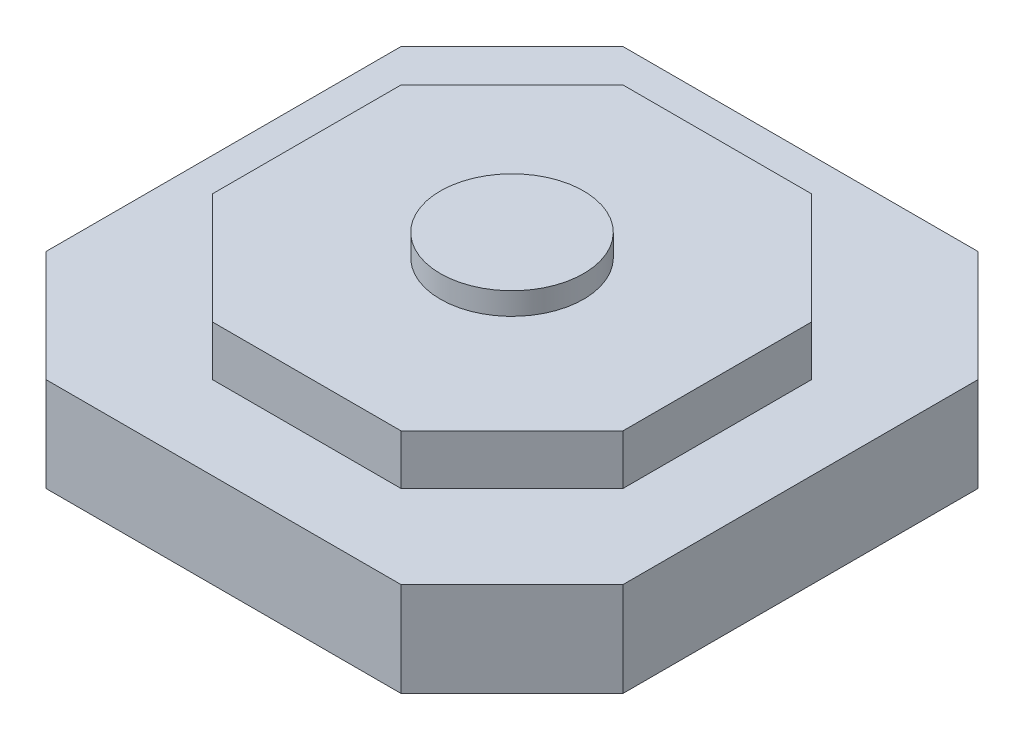
SolidWorks part; units mm, degrees
ref_plane "前视基准面" through (0, 0, 0) normal (0, 0, 1) x (1, 0, 0)
ref_plane "上视基准面" through (0, 0, 0) normal (0, 1, 0) x (1, 0, 0)
ref_plane "右视基准面" through (0, 0, 0) normal (1, 0, 0) x (0, 0, -1)
sketch "草图1" plane through (0, 0, 0) normal (0, 1, 0) x (1, 0, 0)
  line L1 (-2.6, 2.6) -> (2.6, 2.6)
  line L2 (-2.6, 2.6) -> (-2.6, -2.6)
  line L3 (-2.6, -2.6) -> (2.6, -2.6)
  line L4 (2.6, 2.6) -> (2.6, -2.6)
  line L5 (-2.6, 2.6) -> (2.6, -2.6) construction
  line L6 (-2.6, -2.6) -> (2.6, 2.6) construction
  point P0 (0, 0)
  dimension "D1" = 5.2
  dimension "D2" = 5.2
extrude "凸台-拉伸1" add sketch "草图1" along normal blind 0.85
chamfer "倒角1" distance 1 angle 45 4 edges at (-2.6, 0.425, -2.6) (2.6, 0.425, -2.6) (2.6, 0.425, 2.6) (-2.6, 0.425, 2.6)
sketch "草图2" plane through (0, 0.85, 0) normal (0, 1, 0) x (1, 0, 0)
  line L1 (-1.85, 1.85) -> (1.85, 1.85)
  line L2 (-1.85, 1.85) -> (-1.85, -1.85)
  line L3 (-1.85, -1.85) -> (1.85, -1.85)
  line L4 (1.85, 1.85) -> (1.85, -1.85)
  line L5 (-1.85, 1.85) -> (1.85, -1.85) construction
  line L6 (-1.85, -1.85) -> (1.85, 1.85) construction
  point P0 (0, 0)
  dimension "D1" = 3.7
  dimension "D2" = 3.7
extrude "凸台-拉伸2" add sketch "草图2" along normal blind 0.45
chamfer "倒角2" distance 1 angle 45 4 edges at (-1.85, 1.075, 1.85) (1.85, 1.075, 1.85) (1.85, 1.075, -1.85) (-1.85, 1.075, -1.85)
sketch "草图3" plane through (0, 1.3, 0) normal (0, 1, 0) x (1, 0, 0)
  circle A0 centre (0, 0) radius 0.6456
extrude "凸台-拉伸3" add sketch "草图3" along normal blind 0.2
